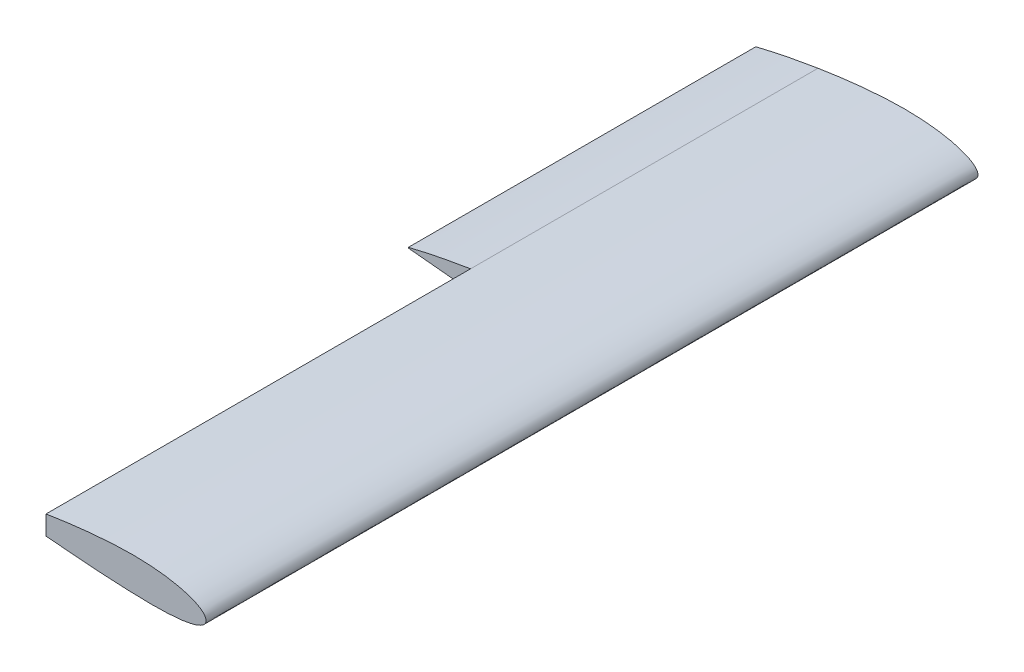
SolidWorks part; units mm, degrees
ref_plane "Front Plane" through (0, 0, 0) normal (0, 0, 1) x (1, 0, 0)
ref_plane "Top Plane" through (0, 0, 0) normal (0, 1, 0) x (1, 0, 0)
ref_plane "Right Plane" through (0, 0, 0) normal (1, 0, 0) x (0, 0, -1)
sketch "Sketch1" plane through (0, 0, 0) normal (0, 0, 1) x (1, 0, 0)
  line L0 (-232.0798, 18.6403) -> (-232.0798, -9.2995)
  spline S0 degree 3 poles (-232.0798, 18.6403) (-229.1643, 19.1051) (-222.2911, 20.2009) (-211.3375, 21.8003) (-199.1467, 23.4589) (-186.7095, 24.9978) (-174.1041, 26.3964) (-161.4086, 27.6282) (-148.7028, 28.67) (-136.0486, 29.4987) (-123.5023, 30.1004) (-111.1413, 30.381) (-99.0664, 30.3378) (-87.3818, 29.9639) (-76.166, 29.2625) (-65.4942, 28.2421) (-55.4376, 26.9176) (-46.0625, 25.3096) (-37.4298, 23.4441) (-29.5941, 21.3513) (-22.603, 19.0647) (-16.4967, 16.6189) (-11.3071, 14.0482) (-7.0567, 11.3833) (-3.7587, 8.6453) (-1.4211, 5.8377) (-0.0765, 2.934) (0.1754, -0.0176) (-0.6552, -2.8586) (-2.5307, -5.4396) (-5.3368, -7.7439) (-9.0399, -9.8146) (-13.6249, -11.6648) (-19.0703, -13.295) (-25.3465, -14.701) (-32.4168, -15.8791) (-40.2393, -16.8276) (-48.7681, -17.5483) (-57.9533, -18.0468) (-67.7426, -18.3331) (-78.0803, -18.4209) (-88.9087, -18.3281) (-100.1673, -18.0756) (-111.7935, -17.6875) (-123.7453, -17.1857) (-135.9735, -16.6041) (-148.4028, -15.8904) (-160.9356, -15.0745) (-173.4784, -14.1779) (-185.9552, -13.2219) (-198.2901, -12.2258) (-210.4075, -11.2062) (-221.6469, -10.2324) (-228.8379, -9.5894) (-232.0798, -9.2995) knots 0 0 0 0 0.018424 0.043434 0.06908 0.095203 0.12164 0.148227 0.1748 0.201195 0.227364 0.253182 0.278347 0.30271 0.326128 0.348467 0.3696 0.389416 0.407811 0.424699 0.440008 0.453688 0.465715 0.476104 0.484928 0.49236 0.49873 0.504587 0.510443 0.516804 0.524199 0.532941 0.543186 0.554996 0.568376 0.583299 0.599709 0.617539 0.636704 0.657109 0.678651 0.701217 0.724685 0.748928 0.773811 0.799338 0.825326 0.851504 0.877716 0.9038 0.929596 0.954944 0.979688 1 1 1 1
extrude "Boss-Extrude1" add sketch "Sketch1" along normal blind 1120
sketch "Sketch2" plane through (0, 0, 0) normal (0, 0, 1) x (1, 0, 0)
  line L0 (-232.0798, 18.6403) -> (-232.0798, -9.2995)
  line L1 (-322.333, 0.5148) -> (-322.333, -0.5066)
  spline S0 degree 3 poles (-232.0798, 18.6403) (-232.9971, 18.4966) (-237.5995, 17.7757) (-245.6979, 16.3987) (-256.1817, 14.5496) (-266.0705, 12.7084) (-275.3065, 10.9119) (-283.8343, 9.1839) (-291.6033, 7.5511) (-298.5679, 6.0388) (-304.6872, 4.6711) (-309.9259, 3.4706) (-314.2535, 2.4578) (-317.6452, 1.6505) (-320.0818, 1.0631) (-321.538, 0.709) (-322.1805, 0.552) (-322.333, 0.5148) knots 0 0 0 0 0.030252 0.151774 0.267626 0.37709 0.479485 0.574175 0.66057 0.73813 0.806369 0.864859 0.913229 0.951173 0.978451 0.994887 1 1 1 1
  spline S1 degree 3 poles (-232.0798, -9.2995) (-232.6657, -9.2475) (-236.9346, -8.868) (-244.7159, -8.1558) (-255.2335, -7.1827) (-265.179, -6.2448) (-274.4894, -5.353) (-283.1057, -4.5145) (-290.9725, -3.7372) (-298.0392, -3.0286) (-304.2602, -2.3953) (-309.5949, -1.8468) (-314.0082, -1.3828) (-317.4721, -1.0277) (-319.9612, -0.741) (-321.4641, -0.6201) (-322.142, -0.5059) (-322.3217, -0.5065) (-322.333, -0.5066) knots 0 0 0 0 0.019463 0.141781 0.258505 0.3689 0.472262 0.567931 0.655294 0.733785 0.802892 0.862162 0.911205 0.949694 0.977373 0.994054 0.999628 1 1 1 1
extrude "Boss-Extrude2" add sketch "Sketch2" along normal blind 504
sketch "Sketch3" plane through (0, 0, 0) normal (0, 0, 1) x (1, 0, 0)
  circle A0 centre (-96.7, 6.044) radius 13
extrude "Cut-Extrude1" cut sketch "Sketch3" along normal blind 801
ref_plane "Plane1" through (0, 0, 330.7) normal (0, 0, 1) x (1, 0, 0)
sketch "Sketch4" plane through (0, 0, 330.7) normal (0, 0, 1) x (1, 0, 0)
  line L0 (-112.7, -19.138) -> (-80.7, -19.138)
  line L1 (-80.7, -19.138) -> (-80.7, 21.744)
  line L2 (-80.7, 21.744) -> (-112.7, 21.744)
  line L3 (-112.7, 21.744) -> (-112.7, -19.138)
extrude "Cut-Extrude2" cut sketch "Sketch4" along normal blind 46
ref_plane "Plane2" through (0, 0, 330.7) normal (0, 0, 1) x (1, 0, 0)
sketch "Sketch5" plane through (0, 0, 330.7) normal (0, 0, 1) x (1, 0, 0)
  line L0 (-287.8664, -8.987) -> (-227.8664, -8.987)
  line L1 (-227.8664, -8.987) -> (-227.8664, 3.013)
  line L2 (-227.8664, 3.013) -> (-287.8664, 3.013)
  line L3 (-287.8664, 3.013) -> (-287.8664, -8.987)
extrude "Cut-Extrude3" cut sketch "Sketch5" along normal blind 46
ref_plane "Plane3" through (0, 0, 534.5) normal (0, 0, 1) x (1, 0, 0)
sketch "Sketch6" plane through (0, 0, 534.5) normal (0, 0, 1) x (1, 0, 0)
  line L0 (-204.283, -16.91) -> (-150.283, -16.91)
  line L1 (-150.283, -16.91) -> (-150.283, 12.19)
  line L2 (-150.283, 12.19) -> (-204.283, 12.19)
  line L3 (-204.283, 12.19) -> (-204.283, -16.91)
extrude "Cut-Extrude4" cut sketch "Sketch6" along normal blind 64
ref_plane "Plane4" through (0, 0, -0.5) normal (0, 0, 1) x (1, 0, 0)
sketch "Sketch7" plane through (0, 0, -0.5) normal (0, 0, 1) x (1, 0, 0)
  line L0 (-235.833, 1.435) -> (-215.433, 1.435)
  line L1 (-215.433, 1.435) -> (-215.433, 8.235)
  line L2 (-215.433, 8.235) -> (-235.833, 8.235)
  line L3 (-235.833, 8.235) -> (-235.833, 1.435)
extrude "Cut-Extrude5" cut sketch "Sketch7" along normal blind 26
